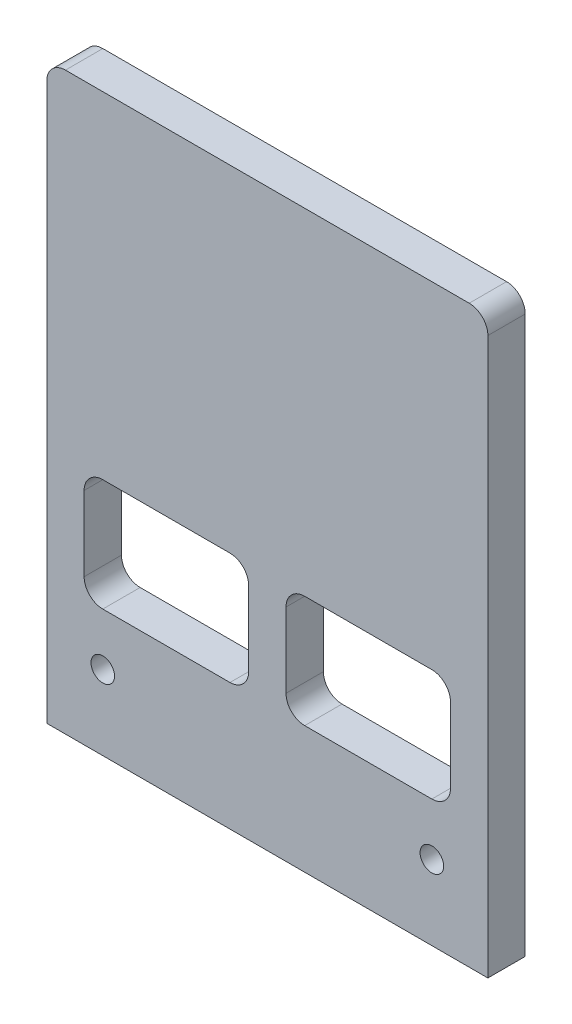
SolidWorks part; units mm, degrees
material "Acrylic (Medium-high impact)"
ref_plane "Front Plane" through (0, 0, 0) normal (0, 0, 1) x (1, 0, 0)
ref_plane "Top Plane" through (0, 0, 0) normal (0, 1, 0) x (1, 0, 0)
ref_plane "Right Plane" through (0, 0, 0) normal (1, 0, 0) x (0, 0, -1)
sketch "Sketch1" plane through (0, 0, 0) normal (0, 0, 1) x (1, 0, 0)
  line L1 (-37.5, -50.475) -> (37.5, -50.475)
  line L2 (-37.5, -50.475) -> (-37.5, 50.475)
  line L3 (-37.5, 50.475) -> (37.5, 50.475)
  line L4 (37.5, -50.475) -> (37.5, 50.475)
  line L5 (-37.5, -50.475) -> (37.5, 50.475) construction
  line L6 (-37.5, 50.475) -> (37.5, -50.475) construction
  point P0 (0, 0)
  dimension "D1" = 75
  dimension "D2" = 100.95
extrude "Boss-Extrude1" add sketch "Sketch1" along normal blind 6.35
sketch "Sketch3" plane through (0, 0, 6.35) normal (0, 0, 1) x (1, 0, 0)
  line L0 (-37.5, 50.475) -> (-37.5, -50.475) construction
  line L1 (-37.5, -50.475) -> (37.5, -50.475) construction
  line L2 (37.5, -50.475) -> (37.5, 50.475) construction
  circle A0 centre (-27.975, -37.775) radius 2
  circle A1 centre (27.975, -37.775) radius 2
  dimension "D1" = 4
  dimension "D2" = 9.525
  dimension "D3" = 12.7
  dimension "D4" = 9.525
extrude "Cut-Extrude1" cut sketch "Sketch3" against normal blind 6.35
sketch "Sketch4" plane through (0, 0, 0) normal (0, 0, -1) x (-1, 0, 0)
  line L0 (-37.5, 47.3) -> (37.5, 47.3)
  line L4 (-37.5, 50.475) -> (-37.5, -50.475)
  line L5 (-37.5, -50.475) -> (37.5, -50.475)
  line L6 (37.5, -50.475) -> (37.5, 50.475)
  line L7 (37.5, 50.475) -> (-37.5, 50.475)
  line L8 (-37.5, 50.475) -> (-37.5, -50.475)
  line L9 (-37.5, -50.475) -> (37.5, -50.475)
  line L10 (37.5, -50.475) -> (37.5, 50.475)
  line L11 (37.5, 50.475) -> (-37.5, 50.475)
  line M8 (-37.5, 50.475) -> (-37.5, -50.475)
  line M10 (37.5, -50.475) -> (37.5, 50.475)
  line M11 (37.5, 50.475) -> (-37.5, 50.475)
  dimension "D2" = 3.175
  dimension "D1" = 0
extrude "Cut-Extrude2" cut sketch "Sketch4" against normal through all contours L0 M8 M10 M11
fillet "Fillet1" radius 3.175 2 edges at (-37.5, 47.3, 3.175) (37.5, 47.3, 3.175)
sketch "Sketch5" plane through (0, 0, 0) normal (0, 0, -1) x (-1, 0, 0)
  line L0 (-37.5, -50.475) -> (-37.5, 44.125) construction
  line L1 (-31.15, -9.835) -> (-3.175, -9.835)
  line L2 (-31.15, -9.835) -> (-31.15, -28.885)
  line L3 (-31.15, -28.885) -> (-3.175, -28.885)
  line L4 (-3.175, -9.835) -> (-3.175, -28.885)
  line L5 (3.175, -9.835) -> (31.15, -9.835)
  line L6 (3.175, -9.835) -> (3.175, -28.885)
  line L7 (3.175, -28.885) -> (31.15, -28.885)
  line L8 (31.15, -9.835) -> (31.15, -28.885)
  circle A0 centre (-27.975, -37.775) radius 2 construction
  dimension "D1" = 6.35
  dimension "D2" = 8.89
  dimension "D3" = 6.35
  dimension "D4" = 3.175
  dimension "D5" = 19.05
extrude "Cut-Extrude3" cut sketch "Sketch5" against normal through all
fillet "Fillet2" radius 3.175 8 edges at (-31.15, -28.885, 3.175) (-31.15, -9.835, 3.175) (-3.175, -9.835, 3.175) (-3.175, -28.885, 3.175) (3.175, -28.885, 3.175) (3.175, -9.835, 3.175) (31.15, -9.835, 3.175) (31.15, -28.885, 3.175)
